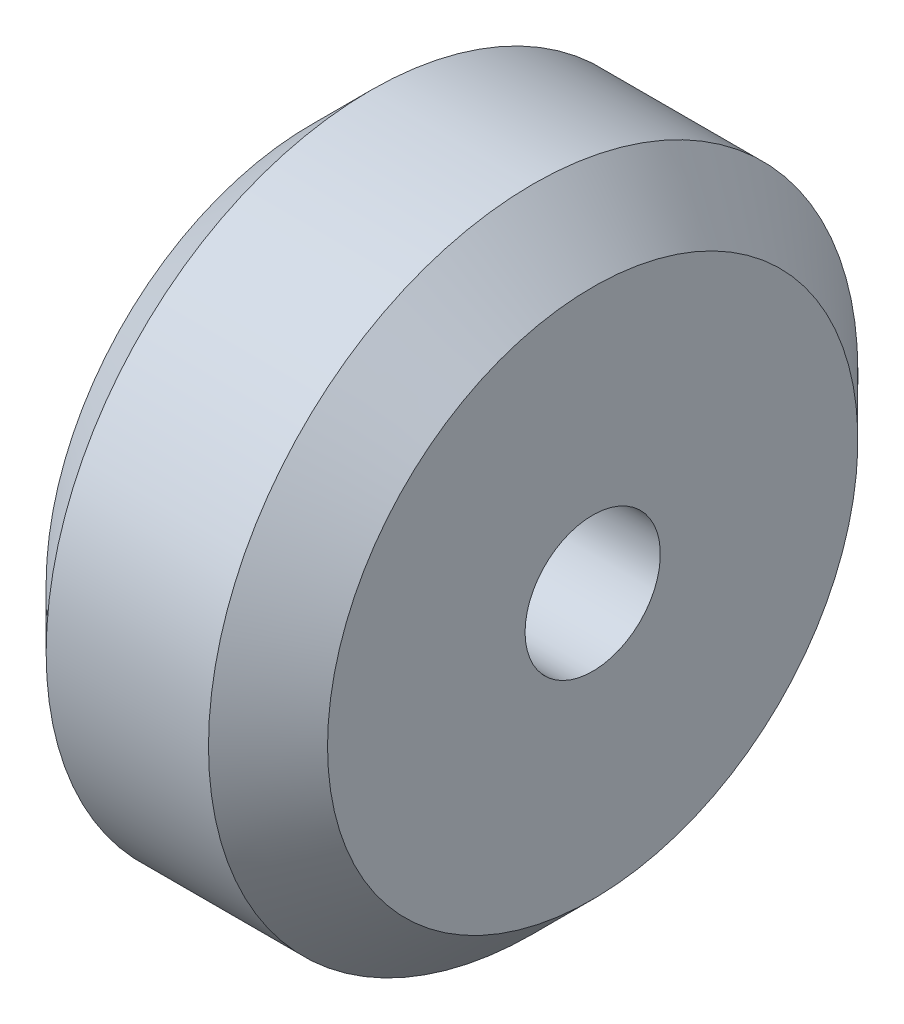
SolidWorks part; units mm, degrees
ref_plane "Alzado" through (0, 0, 0) normal (0, 0, 1) x (1, 0, 0)
ref_plane "Planta" through (0, 0, 0) normal (0, 1, 0) x (1, 0, 0)
ref_plane "Vista lateral" through (0, 0, 0) normal (1, 0, 0) x (0, 0, -1)
sketch "Croquis1" plane through (0, 0, 0) normal (0, 0, 1) x (1, 0, 0)
  line L0 (-5.2, 0) -> (5.2, 0) construction
  line L1 (-3, 12) -> (3, 12)
  line L3 (-5.2, 2.5) -> (-5.2, 9.8)
  line L6 (-3, 12) -> (3, 12)
  line L10 (-5.2, 2.5) -> (5.2, 2.5)
  line L11 (-3, 12) -> (-5.2, 9.8)
  line L12 (3, 12) -> (5.2, 9.8)
  line L14 (5.2, 2.5) -> (5.2, 9.8)
revolve "Revolución2" add sketch "Croquis1" angle 360 about L0
